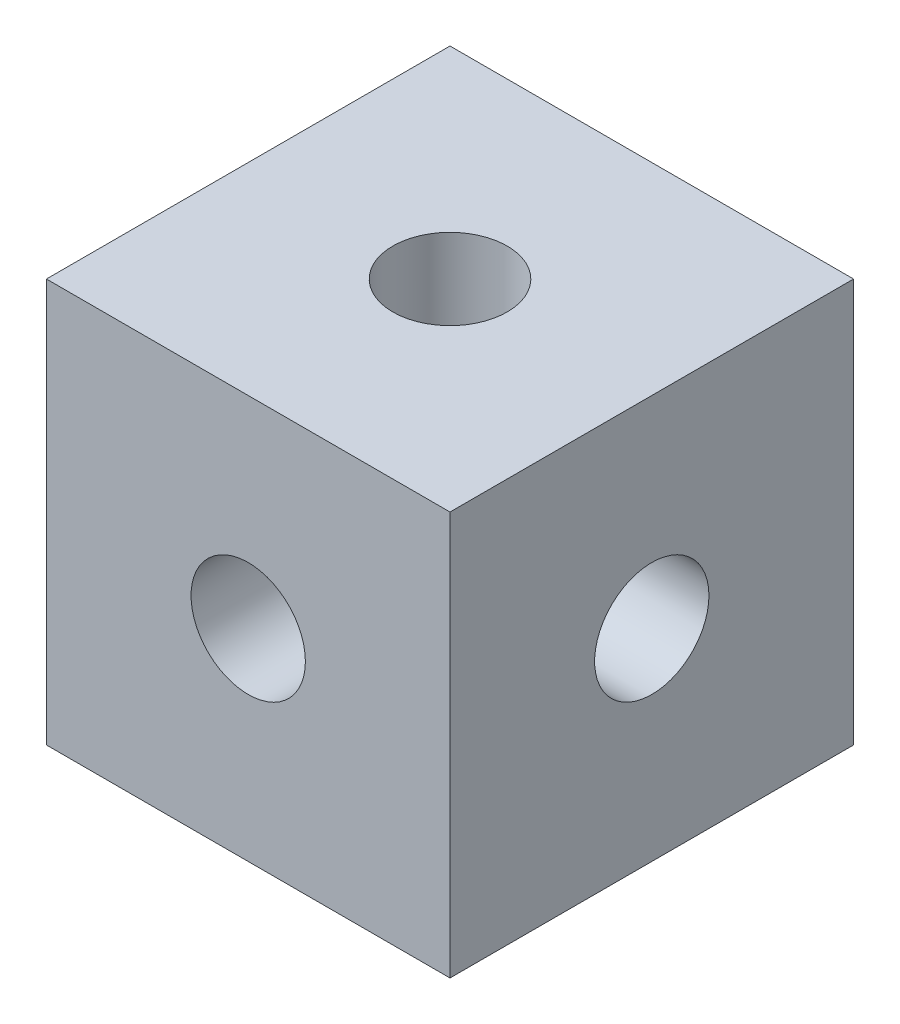
SolidWorks part; units mm, degrees
material "1060 Alloy"
ref_plane "Front Plane" through (0, 0, 0) normal (0, 0, 1) x (1, 0, 0)
ref_plane "Top Plane" through (0, 0, 0) normal (0, 1, 0) x (1, 0, 0)
ref_plane "Right Plane" through (0, 0, 0) normal (1, 0, 0) x (0, 0, -1)
sketch "Sketch1" plane through (0, 0, 0) normal (0, 1, 0) x (1, 0, 0)
  line L1 (-6, -6) -> (6, -6)
  line L2 (-6, -6) -> (-6, 6)
  line L3 (-6, 6) -> (6, 6)
  line L4 (6, -6) -> (6, 6)
  line L5 (-6, -6) -> (6, 6) construction
  line L6 (-6, 6) -> (6, -6) construction
  point P0 (0, 0)
  dimension "D1" = 12
  dimension "D2" = 12
extrude "Boss-Extrude1" add sketch "Sketch1" along normal blind 12
hole_wizard "M3 Clearance Hole1" positions "Sketch2" profile "Sketch3" hole size "M3" standard "ANSI Metric" end condition through all
sketch "Sketch2" plane through (0, 0, 6) normal (0, 0, 1) x (1, 0, 0)
  line L0 (-6, 12) -> (-6, 0) construction
  line L1 (-6, 0) -> (6, 0) construction
  point P0 (0, 6)
  dimension "D1" = 6
  dimension "D2" = 6
sketch "Sketch3" plane through (0, 6, 6) normal (1, 0, 0) x (0, -1, 0)
  line L0 (0, 0) -> (0, 12)
  line L1 (0, 12) -> (1.7, 12)
  line L2 (1.7, 12) -> (1.7, 0)
  line L5 (1.7, 0) -> (0, 0)
  line L11 (0, -6.35) -> (0, 107.95) construction
  dimension "Thru Hole Dia." = 3.4
  dimension "Thru Hole Depth" = 12
hole_wizard "M3 Clearance Hole2" positions "Sketch4" profile "Sketch5" hole size "M3" standard "ANSI Metric" end condition through all
sketch "Sketch4" plane through (6, 0, 0) normal (1, 0, 0) x (0, 0, -1)
  line L0 (-6, 0) -> (6, 0) construction
  line L1 (-6, 12) -> (-6, 0) construction
  point P0 (0, 6)
  dimension "D1" = 6
  dimension "D2" = 6
sketch "Sketch5" plane through (6, 6, 0) normal (0, 1, 0) x (0, 0, -1)
  line L0 (0, 0) -> (0, 12)
  line L1 (0, 12) -> (1.7, 12)
  line L2 (1.7, 12) -> (1.7, 0)
  line L5 (1.7, 0) -> (0, 0)
  line L11 (0, -6.35) -> (0, 107.95) construction
  dimension "Thru Hole Dia." = 3.4
  dimension "Thru Hole Depth" = 12
hole_wizard "M3 Clearance Hole3" positions "Sketch6" profile "Sketch7" hole size "M3" standard "ANSI Metric" end condition through all
sketch "Sketch6" plane through (0, 12, 0) normal (0, 1, 0) x (1, 0, 0)
  point P0 (0, 0)
sketch "Sketch7" plane through (0, 12, 0) normal (1, 0, 0) x (0, 0, 1)
  line L0 (0, 0) -> (0, 12)
  line L1 (0, 12) -> (1.7, 12)
  line L2 (1.7, 12) -> (1.7, 0)
  line L5 (1.7, 0) -> (0, 0)
  line L11 (0, -6.35) -> (0, 107.95) construction
  dimension "Thru Hole Dia." = 3.4
  dimension "Thru Hole Depth" = 12
